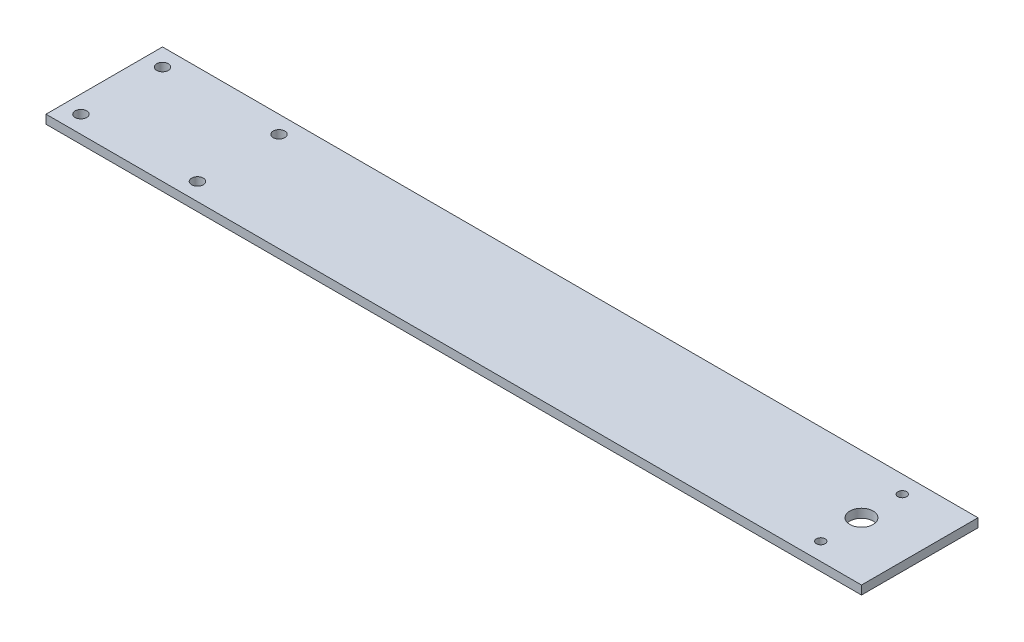
SolidWorks part; units mm, degrees
ref_plane "Front Plane" through (0, 0, 0) normal (0, 0, 1) x (1, 0, 0)
ref_plane "Top Plane" through (0, 0, 0) normal (0, 1, 0) x (1, 0, 0)
ref_plane "Right Plane" through (0, 0, 0) normal (1, 0, 0) x (0, 0, -1)
sketch "Sketch1" plane through (0, 0, 0) normal (0, 1, 0) x (1, 0, 0)
  line L0 (-140, 0) -> (140, 0) construction
  line L1 (-140, 20) -> (140, 20)
  line L2 (-140, 20) -> (-140, -20)
  line L3 (-140, -20) -> (140, -20)
  line L4 (140, 20) -> (140, -20)
  line L5 (-140, 20) -> (140, -20) construction
  line L6 (-140, -20) -> (140, 20) construction
  line L7 (0, 20) -> (0, -20) construction
  line L8 (-134, 14) -> (-94, 14) construction
  line L9 (-134, 14) -> (-134, -14) construction
  line L10 (-134, -14) -> (-94, -14) construction
  line L11 (-94, 14) -> (-94, -14) construction
  line L12 (-134, 14) -> (-94, -14) construction
  line L13 (-134, -14) -> (-94, 14) construction
  line L14 (120, 20) -> (120, -20) construction
  circle A0 centre (-134, 14) radius 2
  circle A1 centre (-94, 14) radius 2
  circle A2 centre (-94, -14) radius 2
  circle A3 centre (-134, -14) radius 2
  circle A8 centre (120, 0) radius 4
  circle A9 centre (120, 14) radius 1.5
  circle A10 centre (120, -14) radius 1.5
  point P0 (0, 0)
  point P8 (-114, 0)
  point P20 (0, 0)
  point P25 (120, 0)
  dimension "D6" = 4
  dimension "D7" = 4
  dimension "D8" = 4
  dimension "D9" = 4
  dimension "D10" = 8
  dimension "D11" = 20
  dimension "D12" = 3
  dimension "D13" = 3
  dimension "D14" = 6
  dimension "D15" = 6
  dimension "D1" = 280
  dimension "D2" = 40
  dimension "D3" = 40
  dimension "D4" = 28
  dimension "D5" = 6
extrude "Boss-Extrude1" add sketch "Sketch1" along normal blind 3
